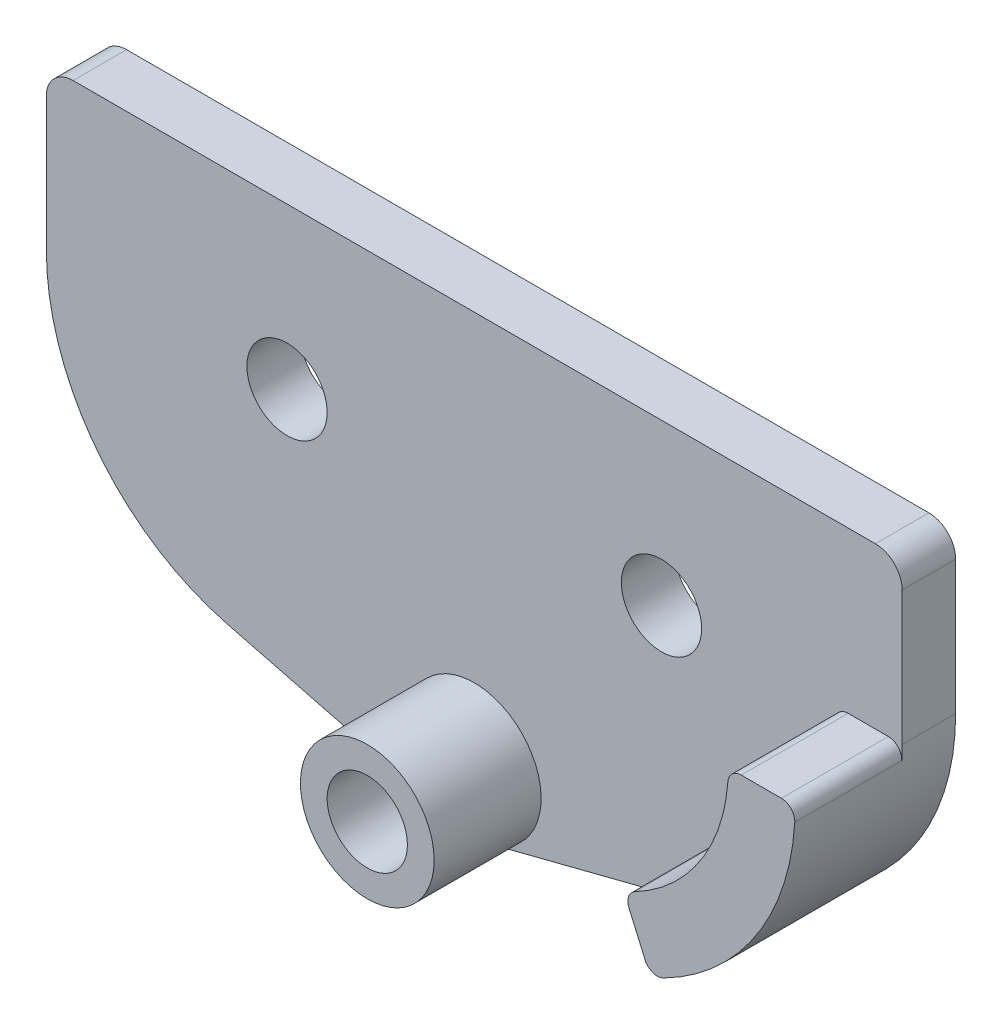
SolidWorks part; units mm, degrees
ref_plane "前视基准面" through (0, 0, 0) normal (0, 0, 1) x (1, 0, 0)
ref_plane "上视基准面" through (0, 0, 0) normal (0, 1, 0) x (1, 0, 0)
ref_plane "右视基准面" through (0, 0, 0) normal (1, 0, 0) x (0, 0, -1)
sketch "草图2" plane through (0, 0, 0) normal (0, 0, 1) x (1, 0, 0)
  line L0 (0, 6.5192) -> (0, -8.5) construction
  line L1 (0, 0) -> (7, 0) construction
  line L2 (0, -6) -> (7, -6) construction
  line L3 (7, 6) -> (-7, 6)
  line L4 (16, 0) -> (16, 6)
  line L5 (16, 6) -> (7, 6)
  line L6 (9.2305, -8.7192) -> (0.6196, -10.922)
  line L7 (0, -8.5) -> (0, -16) construction
  line L8 (-9.2305, -8.7192) -> (-0.6196, -10.922)
  line L9 (-16, 0) -> (-16, 6)
  line L10 (-16, 6) -> (-7, 6)
  circle A0 centre (7, 0) radius 6 construction
  circle A1 centre (0, -8.5) radius 1.5
  circle A2 centre (7, 0) radius 1.5
  circle A5 centre (0, -8.5) radius 2.5 construction
  arc A6 (9.2305, -8.7192) -> (16, 0) centre (7, 0) ccw
  arc A7 (0.6196, -10.922) -> (-0.6196, -10.922) centre (0, -8.5) cw
  circle A8 centre (-7, 0) radius 1.5
  arc A9 (-9.2305, -8.7192) -> (-16, 0) centre (-7, 0) cw
  point P25 (0, 6)
  dimension "D2" = 12
  dimension "D3" = 3
  dimension "D5" = 3
  dimension "D6" = 9
  dimension "D7" = 5
  dimension "D1" = 7
  dimension "D4" = 2.5
extrude "凸台-拉伸1" add sketch "草图2" along normal blind 2
sketch "草图3" plane through (0, 0, 2) normal (0, 0, 1) x (1, 0, 0)
  line L3 (13.5, 0) -> (16, 0)
  line L4 (7, 0) -> (10.5919, -8.2522) construction
  line L5 (9.5942, -5.9599) -> (10.5919, -8.2522)
  arc A0 (9.5942, -5.9599) -> (13.5, 0) centre (7, 0) ccw
  arc A2 (10.5919, -8.2522) -> (16, 0) centre (7, 0) ccw
  dimension "D1" = 13
  dimension "D2" = 9
extrude "凸台-拉伸2" add sketch "草图3" along normal blind 4
fillet "圆角1" radius 1 2 edges at (-16, 6, 1) (16, 6, 1)
fillet "圆角4" radius 0.5 4 edges at (9.5942, -5.9599, 4) (10.5919, -8.2522, 4) (16, 0, 4) (13.5, 0, 4)
sketch "草图4" plane through (0, 0, 2) normal (0, 0, 1) x (1, 0, 0)
  circle A0 centre (0, -8.5) radius 2.5
  circle A1 centre (0, -8.5) radius 1.5
  dimension "D1" = 5
  dimension "D2" = 3
extrude "凸台-拉伸3" add sketch "草图4" along normal blind 4
